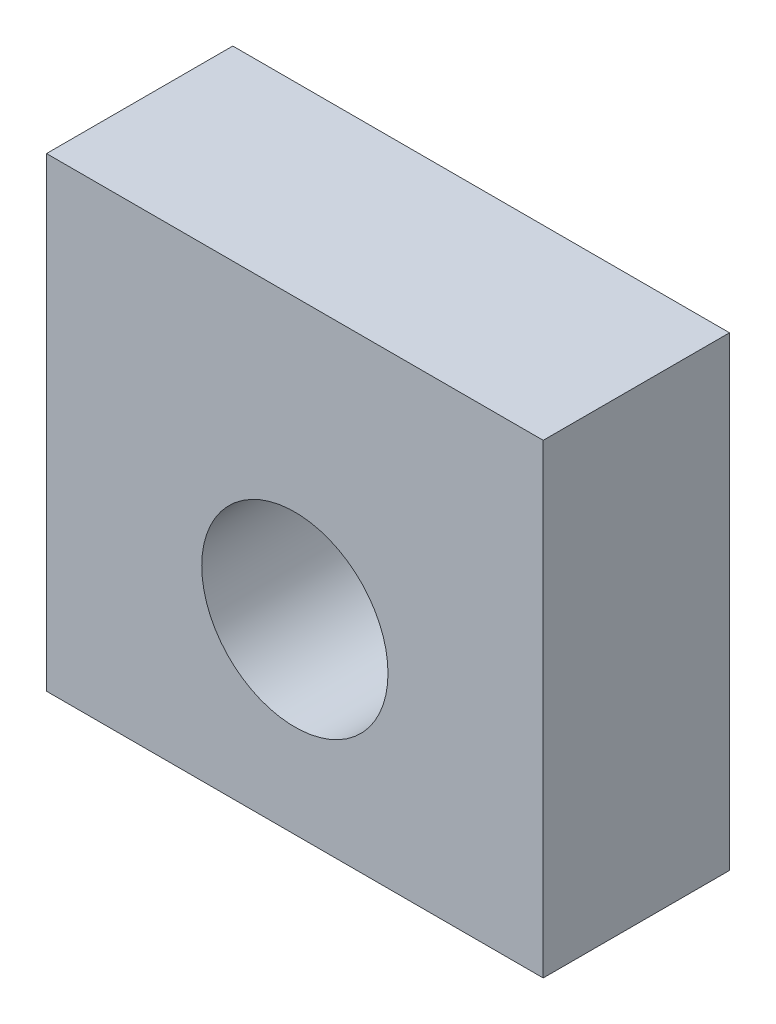
SolidWorks part; units mm, degrees
ref_plane "Plano frontal" through (0, 0, 0) normal (0, 0, 1) x (1, 0, 0)
ref_plane "Plano superior" through (0, 0, 0) normal (0, 1, 0) x (1, 0, 0)
ref_plane "Plano direito" through (0, 0, 0) normal (1, 0, 0) x (0, 0, -1)
sketch "Esboço1" plane through (0, 0, 0) normal (0, 0, 1) x (1, 0, 0)
  line L1 (4, -3.75) -> (-4, -3.75)
  line L2 (4, -3.75) -> (4, 3.75)
  line L3 (4, 3.75) -> (-4, 3.75)
  line L4 (-4, -3.75) -> (-4, 3.75)
  circle A1 centre (0, -0.75) radius 1.5
  dimension "D3" = 3
  dimension "D4" = 4.5
  dimension "D1" = 7.5
  dimension "D2" = 8
extrude "Ressalto-extrusão1" add sketch "Esboço1" along normal blind 3
